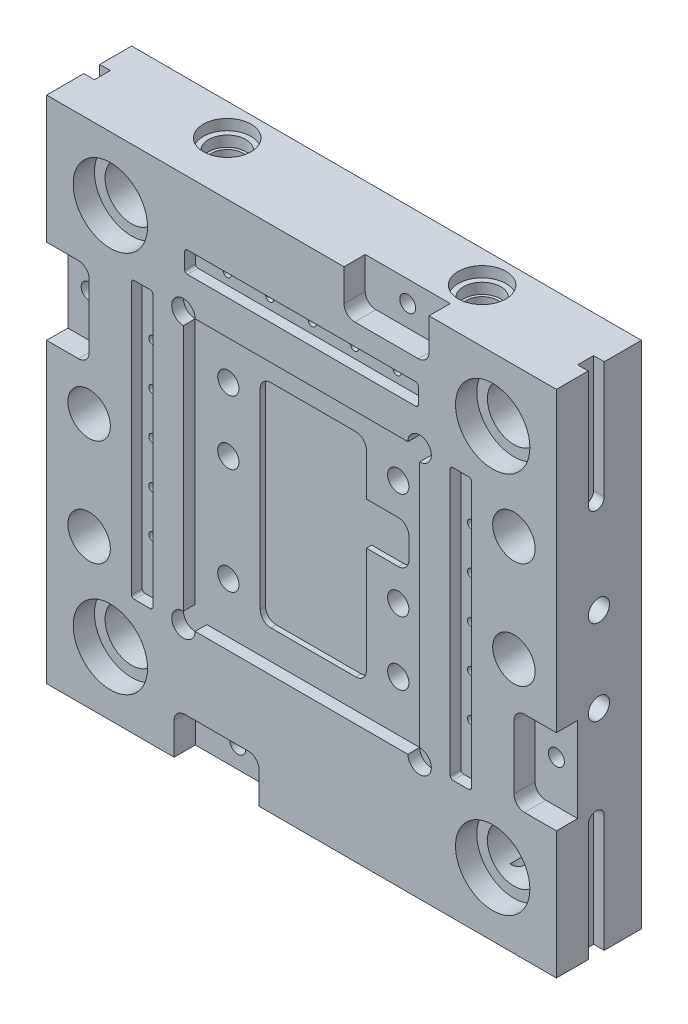
SolidWorks part; units mm, degrees
ref_plane "Plane1" through (0, 0, 0) normal (0, 0, 1) x (1, 0, 0)
ref_plane "Plane2" through (0, 0, 0) normal (0, 1, 0) x (1, 0, 0)
ref_plane "Plane3" through (0, 0, 0) normal (1, 0, 0) x (0, 0, -1)
sketch "Sketch1" plane through (0, 0, 0) normal (0, 0, 1) x (1, 0, 0)
  line L0 (-152.4, 152.4) -> (152.4, 152.4)
  line L1 (-152.4, 152.4) -> (-152.4, -152.4)
  line L2 (152.4, -152.4) -> (-152.4, -152.4)
  line L3 (152.4, -152.4) -> (152.4, 152.4)
  dimension "D1" = 304.8
  dimension "D2" = 304.8
  dimension "D3" = 152.4
  dimension "D4" = 152.4
extrude "Base-Extrude" add sketch "Sketch1" against normal blind 50.8
sketch "Sketch2" plane through (0, 0, 0) normal (0, 0, 1) x (1, 0, 0)
  line L0 (-63.6187, 80.9371) -> (63.6187, 80.9371)
  line L1 (-70.612, 73.9438) -> (-70.612, -73.9438)
  line L2 (63.6187, -80.9371) -> (-63.6187, -80.9371)
  line L3 (70.612, -73.9438) -> (70.612, 73.9438)
  arc A0 (70.612, 73.9438) -> (63.6187, 80.9371) centre (70.612, 80.9371) ccw
  arc A1 (-63.6187, 80.9371) -> (-70.612, 73.9438) centre (-70.612, 80.9371) ccw
  arc A2 (-70.612, -73.9438) -> (-63.6187, -80.9371) centre (-70.612, -80.9371) ccw
  arc A3 (63.6187, -80.9371) -> (70.612, -73.9438) centre (70.612, -80.9371) ccw
  dimension "D1" = 161.8742
  dimension "D2" = 141.224
  dimension "D3" = 70.612
  dimension "D4" = 80.9371
extrude "Cut-Extrude1" cut sketch "Sketch2" against normal blind 7.0358
sketch "Sketch3" plane through (0, 0, 0) normal (0, 0, 1) x (1, 0, 0)
  circle A0 centre (-114.3, 114.3) radius 15.875
  circle A1 centre (114.3, 114.3) radius 15.875
  circle A2 centre (114.3, -114.3) radius 15.875
  circle A3 centre (-114.3, -114.3) radius 15.875
  dimension "D1" = 31.75
extrude "Cut-Extrude2" cut sketch "Sketch3" against normal through all
sketch "Sketch4" plane through (0, 0, 0) normal (0, 0, 1) x (1, 0, 0)
  circle A0 centre (-114.3, 114.3) radius 22.225
  circle A1 centre (114.3, 114.3) radius 22.225
  circle A2 centre (114.3, -114.3) radius 22.225
  circle A3 centre (-114.3, -114.3) radius 22.225
  dimension "D1" = 44.45
extrude "Cut-Extrude3" cut sketch "Sketch4" against normal blind 12.7
sketch "Sketch5" plane through (0, 0, 0) normal (0, 0, 1) x (1, 0, 0)
  line L0 (-76.2, -158.75) -> (-25.4, -158.75)
  line L1 (-76.2, -158.75) -> (-76.2, -133.35)
  line L2 (-31.75, -127) -> (-69.85, -127)
  line L3 (-25.4, -133.35) -> (-25.4, -158.75)
  line L4 (76.2, 158.75) -> (25.4, 158.75)
  line L5 (76.2, 158.75) -> (76.2, 133.35)
  line L6 (31.75, 127) -> (69.85, 127)
  line L7 (25.4, 133.35) -> (25.4, 158.75)
  line L8 (158.75, -76.2) -> (133.35, -76.2)
  line L9 (158.75, -76.2) -> (158.75, -25.4)
  line L10 (133.35, -25.4) -> (158.75, -25.4)
  line L11 (127, -31.75) -> (127, -69.85)
  line L12 (-165.1, 76.2) -> (-133.35, 76.2)
  line L13 (-165.1, 76.2) -> (-165.1, 25.4)
  line L14 (-133.35, 25.4) -> (-165.1, 25.4)
  line L15 (-127, 31.75) -> (-127, 69.85)
  arc A0 (-69.85, -127) -> (-76.2, -133.35) centre (-69.85, -133.35) ccw
  arc A1 (-25.4, -133.35) -> (-31.75, -127) centre (-31.75, -133.35) ccw
  arc A2 (127, -69.85) -> (133.35, -76.2) centre (133.35, -69.85) ccw
  arc A3 (127, -31.75) -> (133.35, -25.4) centre (133.35, -31.75) cw
  arc A4 (69.85, 127) -> (76.2, 133.35) centre (69.85, 133.35) ccw
  arc A5 (25.4, 133.35) -> (31.75, 127) centre (31.75, 133.35) ccw
  arc A6 (-127, 69.85) -> (-133.35, 76.2) centre (-133.35, 69.85) ccw
  arc A7 (-127, 31.75) -> (-133.35, 25.4) centre (-133.35, 31.75) cw
  dimension "D1" = 6.35
  dimension "D2" = 6.35
extrude "Cut-Extrude4" cut sketch "Sketch5" against normal blind 12.7
sketch "Sketch6" plane through (0, 0, -7.0358) normal (0, 0, 1) x (1, 0, 0)
  circle A0 centre (-50.8, 50.8) radius 6.35
  circle A1 centre (50.8, 50.8) radius 6.35
  circle A2 centre (50.8, -50.8) radius 6.35
  circle A3 centre (-50.8, -50.8) radius 6.35
  circle A4 centre (-50.8, 12.7) radius 6.35
  circle A5 centre (50.8, -12.7) radius 6.35
extrude "Cut-Extrude5" cut sketch "Sketch6" against normal through all
sketch "Sketch7" plane through (0, 0, -50.8) normal (0, 0, -1) x (-1, 0, 0)
  circle A0 centre (-50.8, 50.8) radius 11.1125
  circle A1 centre (-50.8, -50.8) radius 11.1125
  circle A2 centre (50.8, -50.8) radius 11.1125
  circle A3 centre (50.8, 50.8) radius 11.1125
  dimension "D1" = 22.225
extrude "Cut-Extrude6" cut sketch "Sketch7" against normal blind 12.7
sketch "Sketch8" plane through (0, 0, -12.7) normal (0, 0, 1) x (1, 0, 0)
  circle A0 centre (-50.8, -139.7) radius 4.7625
  circle A1 centre (-139.7, 50.8) radius 4.7625
  circle A2 centre (50.8, 139.7) radius 4.7625
  circle A3 centre (139.7, -50.8) radius 4.7625
  dimension "D1" = 9.525
extrude "Cut-Extrude7" cut sketch "Sketch8" against normal through all
sketch "Sketch9" plane through (152.4, 0, 0) normal (1, 0, 0) x (0, 0, -1)
  line L1 (28.6004, -82.55) -> (28.6004, -158.75)
  line L2 (19.05, -158.75) -> (28.6004, -158.75)
  line L3 (19.05, -158.75) -> (19.05, -82.55)
  line L4 (19.05, 158.75) -> (28.6004, 158.75)
  line L5 (19.05, 158.75) -> (19.05, 82.55)
  line L7 (28.6004, 82.55) -> (28.6004, 158.75)
  arc A0 (19.05, -82.55) -> (28.6004, -82.55) centre (23.8252, -82.55) cw
  arc A2 (28.6004, 82.55) -> (19.05, 82.55) centre (23.8252, 82.55) cw
extrude "Cut-Extrude9" cut sketch "Sketch9" against normal blind 6.35
sketch "Sketch10" plane through (-152.4, 0, 0) normal (-1, 0, 0) x (0, 0, 1)
  line L1 (-30.1625, -82.55) -> (-30.1625, -158.75)
  line L2 (-20.6375, -158.75) -> (-30.1625, -158.75)
  line L3 (-20.6375, -158.75) -> (-20.6375, -82.55)
  line L4 (-22.225, 165.1) -> (-31.75, 165.1)
  line L5 (-22.225, 165.1) -> (-22.225, 82.5246)
  line L7 (-31.75, 82.5246) -> (-31.75, 165.1)
  arc A0 (-22.225, 82.5246) -> (-31.75, 82.5246) centre (-26.9875, 82.5246) cw
  arc A1 (-30.1625, -82.55) -> (-20.6375, -82.55) centre (-25.4, -82.55) cw
  dimension "D1" = 4.7625
  dimension "D2" = 4.7625
extrude "Cut-Extrude10" cut sketch "Sketch10" against normal blind 6.35
sketch "Sketch11" plane through (0, 0, 0) normal (0, 0, 1) x (1, 0, 0)
  line L0 (90.4875, 80.9625) -> (100.0125, 80.9625)
  line L1 (88.9, 79.375) -> (88.9, -79.375)
  line L2 (100.0125, -80.9625) -> (90.4875, -80.9625)
  line L3 (101.6, -79.375) -> (101.6, 79.375)
  line L4 (-90.4875, 82.55) -> (-100.0125, 82.55)
  line L5 (-88.9, 80.9625) -> (-88.9, -80.9625)
  line L6 (-100.0125, -82.55) -> (-90.4875, -82.55)
  line L7 (-101.6, -80.9625) -> (-101.6, 80.9625)
  line L8 (-68.2625, 101.6) -> (68.2625, 101.6)
  line L9 (-69.85, 103.1875) -> (-69.85, 112.7125)
  line L10 (68.2625, 114.3) -> (-68.2625, 114.3)
  line L11 (69.85, 112.7125) -> (69.85, 103.1875)
  arc A0 (101.6, -79.375) -> (100.0125, -80.9625) centre (100.0125, -79.375) cw
  arc A1 (90.4875, -80.9625) -> (88.9, -79.375) centre (90.4875, -79.375) cw
  arc A2 (88.9, 79.375) -> (90.4875, 80.9625) centre (90.4875, 79.375) cw
  arc A3 (101.6, 79.375) -> (100.0125, 80.9625) centre (100.0125, 79.375) ccw
  arc A4 (-88.9, 80.9625) -> (-90.4875, 82.55) centre (-90.4875, 80.9625) ccw
  arc A5 (-101.6, 80.9625) -> (-100.0125, 82.55) centre (-100.0125, 80.9625) cw
  arc A6 (-101.6, -80.9625) -> (-100.0125, -82.55) centre (-100.0125, -80.9625) ccw
  arc A7 (-90.4875, -82.55) -> (-88.9, -80.9625) centre (-90.4875, -80.9625) ccw
  arc A8 (-69.85, 103.1875) -> (-68.2625, 101.6) centre (-68.2625, 103.1875) ccw
  arc A9 (-68.2625, 114.3) -> (-69.85, 112.7125) centre (-68.2625, 112.7125) ccw
  arc A10 (69.85, 112.7125) -> (68.2625, 114.3) centre (68.2625, 112.7125) ccw
  arc A11 (69.85, 103.1875) -> (68.2625, 101.6) centre (68.2625, 103.1875) cw
  dimension "D1" = 1.5875
  dimension "D2" = 1.5875
  dimension "D3" = 139.7
  dimension "D4" = 12.7
extrude "Cut-Extrude11" cut sketch "Sketch11" against normal blind 6.35
sketch "Sketch12" plane through (0, 0, -6.35) normal (0, 0, 1) x (1, 0, 0)
  circle A0 centre (0, 107.95) radius 2.3812
  circle A1 centre (-25.4, 107.95) radius 2.3813
  circle A2 centre (-50.8, 107.95) radius 2.3812
  circle A3 centre (25.4, 107.95) radius 2.3813
  circle A4 centre (50.8, 107.95) radius 2.3812
  circle A5 centre (-95.25, 0) radius 2.3813
  circle A6 centre (-95.25, 25.4) radius 2.3813
  circle A7 centre (-95.25, 50.8) radius 2.3813
  circle A8 centre (-95.25, -25.4) radius 2.3813
  circle A9 centre (-95.25, -50.8) radius 2.3813
  circle A10 centre (95.25, 50.8) radius 2.3813
  circle A11 centre (95.25, 25.4) radius 2.3813
  circle A12 centre (95.25, 0) radius 2.3813
  circle A13 centre (95.25, -25.4) radius 2.3813
  circle A14 centre (95.25, -50.8) radius 2.3813
  dimension "D1" = 4.7625
extrude "Cut-Extrude12" cut sketch "Sketch12" against normal through all
sketch "Sketch13" plane through (0, -152.4, 0) normal (0, -1, 0) x (1, 0, 0)
  line L0 (0, -50.8) -> (0, -6.35) construction
  circle A0 centre (0, -25.4) radius 6.35
  circle A1 centre (101.6, -25.4) radius 6.35
  circle A2 centre (-101.6, -25.4) radius 6.35
extrude "Cut-Extrude13" cut sketch "Sketch13" against normal blind 25.4
sketch "Sketch14" plane through (0, 0, -50.8) normal (0, 0, -1) x (-1, 0, 0)
  circle A0 centre (-95.25, 50.8) radius 5.2093
  circle A1 centre (-95.25, 0) radius 5.2093
  circle A2 centre (-95.25, -50.8) radius 5.2093
  circle A3 centre (95.25, -50.8) radius 5.2093
  circle A4 centre (95.25, 0) radius 5.2093
  circle A5 centre (95.25, 50.8) radius 5.2093
  circle A6 centre (50.8, 107.95) radius 5.2093
  circle A8 centre (0, 107.95) radius 5.2093
  circle A9 centre (-50.8, 107.95) radius 5.2093
  dimension "D1" = 10.4186
extrude "Cut-Extrude14" cut sketch "Sketch14" against normal blind 5.08
sketch "Sketch15" plane through (0, 0, 0) normal (0, 0, 1) x (1, 0, 0)
  circle A0 centre (-127, 0) radius 12.7
  circle A1 centre (-127, -63.5) radius 12.7
  circle A2 centre (127, 0) radius 12.7
  circle A3 centre (127, 63.5) radius 12.7
extrude "Cut-Extrude15" cut sketch "Sketch15" against normal blind 19.05
sketch "Sketch16" plane through (0, 0, -19.05) normal (0, 0, 1) x (1, 0, 0)
  circle A0 centre (127, 63.5) radius 3.175
  circle A1 centre (127, 0) radius 3.175
  circle A2 centre (-127, 0) radius 3.175
  circle A3 centre (-127, -63.5) radius 3.175
  dimension "D1" = 6.35
extrude "Cut-Extrude16" cut sketch "Sketch16" against normal blind 25.4
chamfer "Chamfer1" [suppressed] distance 1.5875 angle 45
sketch "Sketch17" plane through (0, 0, -7.0358) normal (0, 0, 1) x (1, 0, 0)
  line L0 (-25.4, 63.5) -> (25.4, 63.5)
  line L1 (-31.75, 57.15) -> (-31.75, -31.75)
  line L2 (25.4, -63.5) -> (-25.4, -63.5)
  line L3 (31.75, -57.15) -> (31.75, 6.35)
  line L8 (31.75, 31.75) -> (50.8, 31.75)
  line L9 (-31.75, -31.75) -> (-31.75, -57.15)
  line L10 (50.8, 6.35) -> (31.75, 6.35)
  line L11 (57.15, 12.7) -> (57.15, 25.4)
  line L12 (31.75, 31.75) -> (31.75, 57.15)
  arc A0 (-25.4, -63.5) -> (-31.75, -57.15) centre (-25.4, -57.15) cw
  arc A1 (31.75, -57.15) -> (25.4, -63.5) centre (25.4, -57.15) cw
  arc A4 (-31.75, 57.15) -> (-25.4, 63.5) centre (-25.4, 57.15) cw
  arc A5 (31.75, 57.15) -> (25.4, 63.5) centre (25.4, 57.15) ccw
  arc A6 (57.15, 25.4) -> (50.8, 31.75) centre (50.8, 25.4) ccw
  arc A7 (57.15, 12.7) -> (50.8, 6.35) centre (50.8, 12.7) cw
  dimension "D1" = 6.35
extrude "Cut-Extrude17" cut sketch "Sketch17" against normal blind 3.175
sketch "Sketch18" plane through (0, -152.4, 0) normal (0, -1, 0) x (1, 0, 0)
  circle A0 centre (-76.2, -31.7754) radius 9.525
  circle A1 centre (76.2, -31.7754) radius 9.525
  dimension "D1" = 19.05
extrude "Cut-Extrude18" cut sketch "Sketch18" against normal blind 241.046
sketch "Sketch19" plane through (0, -152.4, 0) normal (0, -1, 0) x (1, 0, 0)
  circle A0 centre (76.2, -31.7754) radius 11.1125
  circle A1 centre (-76.2, -31.7754) radius 11.1125
  dimension "D1" = 22.225
extrude "Cut-Extrude19" cut sketch "Sketch19" against normal blind 12.7
sketch "Sketch20" plane through (0, -152.4, 0) normal (0, -1, 0) x (1, 0, 0)
  circle A0 centre (76.2, -31.7754) radius 14.2875
  circle A1 centre (-76.2, -31.7754) radius 14.2875
  dimension "D1" = 28.575
extrude "Cut-Extrude20" cut sketch "Sketch20" against normal blind 6.35
sketch "Sketch21" plane through (0, 152.4, 0) normal (0, 1, 0) x (-1, 0, 0)
  circle A0 centre (-76.2, -31.7754) radius 11.1125
  circle A1 centre (76.2, -31.7754) radius 11.1125
  dimension "D1" = 22.225
extrude "Cut-Extrude21" cut sketch "Sketch21" against normal blind 12.7
sketch "Sketch22" plane through (0, 152.4, 0) normal (0, 1, 0) x (-1, 0, 0)
  circle A0 centre (-76.2, -31.7754) radius 14.2875
  circle A1 centre (76.2, -31.7754) radius 14.2875
  dimension "D1" = 28.575
extrude "Cut-Extrude22" cut sketch "Sketch22" against normal blind 6.35
sketch "Sketch23" plane through (152.4, 0, 0) normal (1, 0, 0) x (0, 0, -1)
  circle A0 centre (25.4, 25.4) radius 6.35
  circle A1 centre (25.4, -25.4) radius 6.35
  dimension "D1" = 12.7
extrude "Cut-Extrude23" cut sketch "Sketch23" against normal blind 25.4
sketch "Sketch24" plane through (-152.4, 0, 0) normal (-1, 0, 0) x (0, 0, 1)
  line L0 (-50.8, 25.4) -> (-6.35, 25.4) construction
  line L1 (-50.8, -25.4) -> (-6.35, -25.4) construction
  circle A0 centre (-25.4, 25.4) radius 6.35
  circle A1 centre (-25.4, -25.4) radius 6.35
extrude "Cut-Extrude24" cut sketch "Sketch24" against normal blind 25.4
sketch "Sketch25" plane through (0, 139.7, 0) normal (0, 1, 0) x (-1, 0, 0)
  circle A0 centre (-76.2, -31.7754) radius 9.525
  circle A1 centre (76.2, -31.7754) radius 9.525
  dimension "D1" = 19.05
extrude "Cut-Extrude25" cut sketch "Sketch25" against normal blind 50.8
